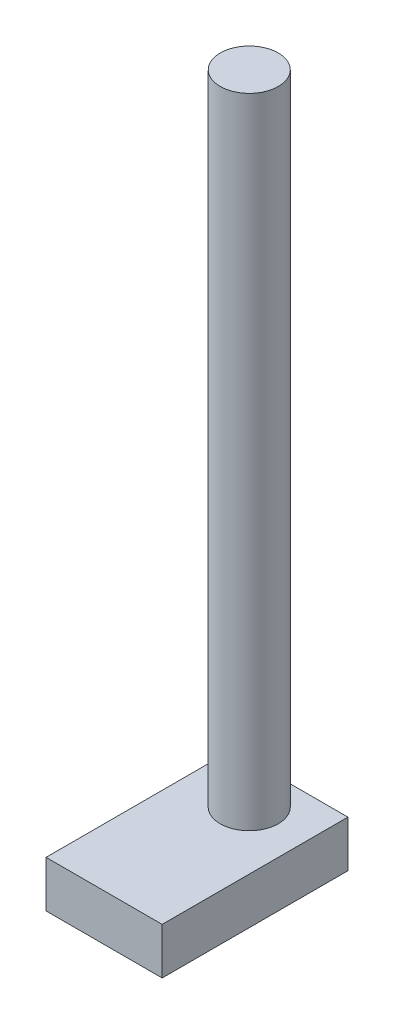
SolidWorks part; units mm, degrees
ref_plane "Front Plane" through (0, 0, 0) normal (0, 0, 1) x (1, 0, 0)
ref_plane "Top Plane" through (0, 0, 0) normal (0, 1, 0) x (1, 0, 0)
ref_plane "Right Plane" through (0, 0, 0) normal (1, 0, 0) x (0, 0, -1)
sketch "Sketch1" plane through (0, 0, 0) normal (0, 1, 0) x (1, 0, 0)
  line L1 (-60.0097, 18.558) -> (39.9903, 18.558)
  line L2 (-60.0097, 18.558) -> (-60.0097, -141.442)
  line L3 (-60.0097, -141.442) -> (39.9903, -141.442)
  line L4 (39.9903, 18.558) -> (39.9903, -141.442)
  dimension "D1" = 100
  dimension "D2" = 160
extrude "Boss-Extrude1" add sketch "Sketch1" along normal blind 40
sketch "Sketch2" plane through (0, 0, 0) normal (0, 1, 0) x (1, 0, 0)
  line L0 (-60.0097, 18.558) -> (39.9903, 18.558) construction
  line L3 (-60.0097, 18.558) -> (-60.0097, -141.442) construction
  circle A0 centre (-10.0097, -16.442) radius 25
  dimension "D1" = 35
  dimension "D2" = 50
  dimension "D3" = 50
extrude "Boss-Extrude2" add sketch "Sketch2" along normal blind 590
